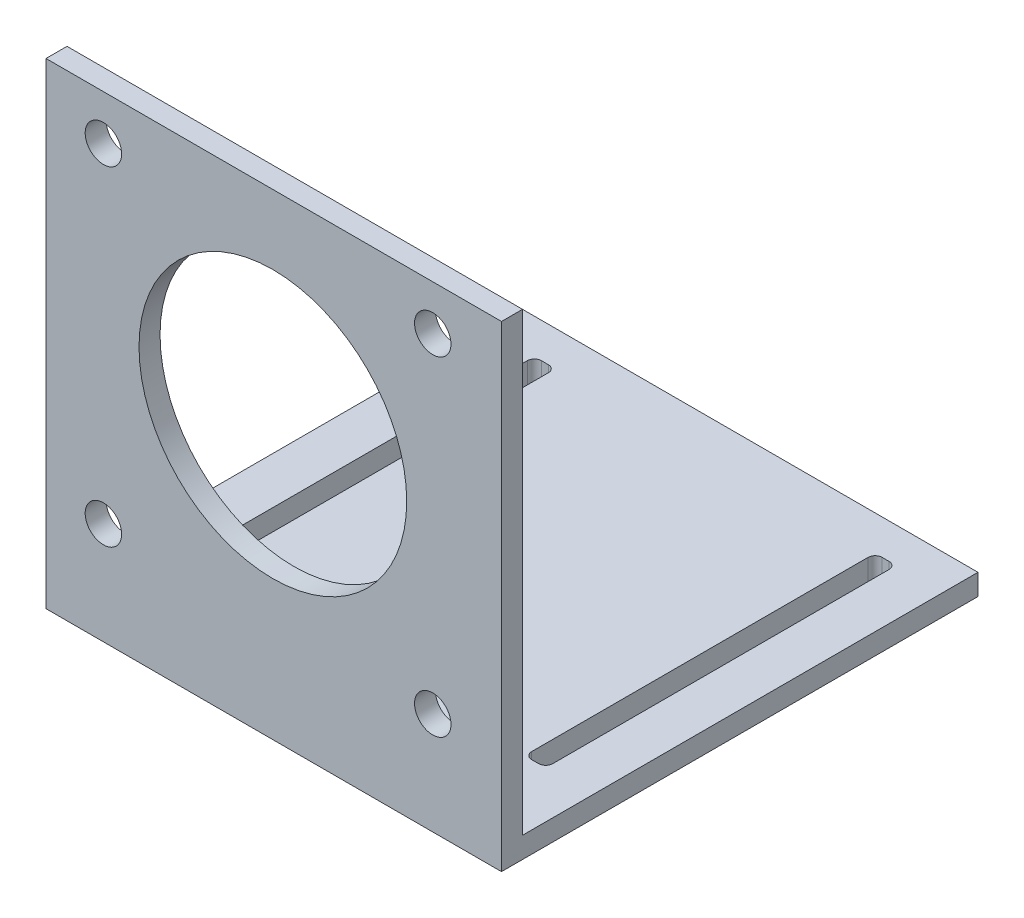
SolidWorks part; units mm, degrees
material "1023 碳钢板 (SS)"
ref_plane "前视基准面" through (0, 0, 0) normal (0, 0, 1) x (1, 0, 0)
ref_plane "上视基准面" through (0, 0, 0) normal (0, 1, 0) x (1, 0, 0)
ref_plane "右视基准面" through (0, 0, 0) normal (1, 0, 0) x (0, 0, -1)
other "Configuration Table"
sketch "草图1" plane through (0, 0, 0) normal (1, 0, 0) x (0, 0, -1)
  line L0 (-6.7062, 58.3349) -> (-6.7062, -9.6651)
  line L1 (-6.7062, -9.6651) -> (61.2938, -9.6651)
  line L2 (61.2938, -9.6651) -> (61.2938, -6.6651)
  line L3 (61.2938, -6.6651) -> (-3.7062, -6.6651)
  line L4 (-3.7062, -6.6651) -> (-3.7062, 58.3349)
  line L5 (-3.7062, 58.3349) -> (-6.7062, 58.3349)
  dimension "D1" = 3
  dimension "D2" = 68
  dimension "D3" = 3
  dimension "D4" = 68
extrude "凸台-拉伸1" add sketch "草图1" along normal blind 65
sketch "草图2" plane through (0, 0, 6.7062) normal (0, 0, 1) x (1, 0, 0)
  line L0 (-27.1129, 29.3349) -> (53.4801, 29.3349) construction
  line L1 (32.375, -3.6207) -> (32.375, 61.046) construction
  line L2 (65, 58.3349) -> (0, 58.3349) construction
  circle A0 centre (32.375, 29.3349) radius 19.1
  circle A1 centre (8.1909, 51.9257) radius 2.6
  circle A2 centre (55.1909, 51.9257) radius 2.6
  circle A3 centre (8.1909, 4.9257) radius 2.6
  circle A4 centre (55.1909, 4.9257) radius 2.6
  dimension "D1" = 29
  dimension "D2" = 47
  dimension "D3" = 47
extrude "切除-拉伸1" cut sketch "草图2" against normal blind 65
sketch "草图3" plane through (0, -6.6651, 0) normal (0, 1, 0) x (1, 0, 0)
  line L0 (8.19, 61.2938) -> (8.19, -27.4852) construction
  line L1 (65, 61.2938) -> (0, 61.2938) construction
  line L2 (56.81, 61.2938) -> (56.81, -64.9994) construction
  line L3 (0, 61.2938) -> (0, -3.7062) construction
  line L4 (65, 61.2938) -> (65, -3.7062) construction
  line L5 (65, -3.7062) -> (0, -3.7062) construction
  line L6 (6.69, 56.2938) -> (9.69, 56.2938)
  line L7 (6.69, 56.2938) -> (6.69, 6.2938)
  line L8 (6.69, 6.2938) -> (9.69, 6.2938)
  line L9 (9.69, 56.2938) -> (9.69, 6.2938)
  line L10 (55.31, 56.2938) -> (58.31, 56.2938)
  line L11 (55.31, 56.2938) -> (55.31, 6.2938)
  line L12 (55.31, 6.2938) -> (58.31, 6.2938)
  line L13 (58.31, 56.2938) -> (58.31, 6.2938)
  dimension "D1" = 8.19
  dimension "D2" = 8.19
  dimension "D3" = 5
  dimension "D4" = 5
  dimension "D5" = 10
  dimension "D6" = 10
  dimension "D7" = 1.5
  dimension "D8" = 1.5
  dimension "D9" = 1.5
  dimension "D10" = 1.5
extrude "切除-拉伸2" cut sketch "草图3" against normal blind 10
fillet "圆角1" radius 1 8 edges at (9.69, -8.1651, -6.2938) (6.69, -8.1651, -6.2938) (9.69, -8.1651, -56.2938) (6.69, -8.1651, -56.2938) (55.31, -8.1651, -56.2938) (58.31, -8.1651, -56.2938) (55.31, -8.1651, -6.2938) (58.31, -8.1651, -6.2938)
